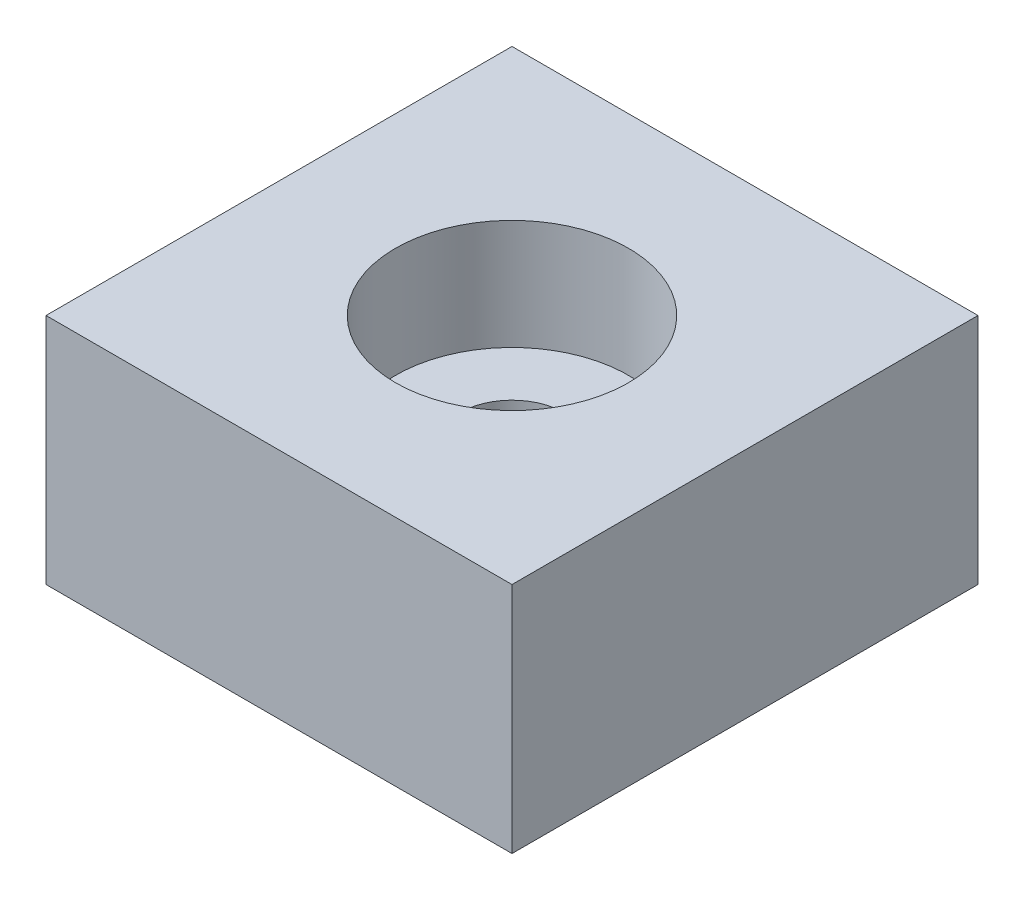
SolidWorks part; units mm, degrees
material "AISI 1020 Steel, Cold Rolled"
ref_plane "Front Plane" through (0, 0, 0) normal (0, 0, 1) x (1, 0, 0)
ref_plane "Top Plane" through (0, 0, 0) normal (0, 1, 0) x (1, 0, 0)
ref_plane "Right Plane" through (0, 0, 0) normal (1, 0, 0) x (0, 0, -1)
sketch "Sketch1" plane through (0, 0, 0) normal (0, 1, 0) x (1, 0, 0)
  line L1 (-19.05, -19.05) -> (19.05, -19.05)
  line L2 (-19.05, -19.05) -> (-19.05, 19.05)
  line L3 (-19.05, 19.05) -> (19.05, 19.05)
  line L4 (19.05, -19.05) -> (19.05, 19.05)
  line L5 (0, 19.05) -> (0, -19.05) construction
  line L6 (-19.05, 0) -> (19.05, 0) construction
  point P0 (0, 0)
  dimension "D1" = 38.1
extrude "Boss-Extrude1" add sketch "Sketch1" along normal blind 19.05
sketch "Sketch4" plane through (0, 19.05, 0) normal (0, 1, 0) x (1, 0, 0)
  point P0 (0, 0)
hole_wizard "M10x1.5 Tapped Hole1" positions "Sketch4" profile "Sketch3" tap size "M10x1.5" standard "ANSI Metric" end condition through all
sketch "Sketch3" plane through (0, 19.05, 0) normal (1, 0, 0) x (0, 0, 1)
  line L0 (0, 0) -> (0, 19.05)
  line L1 (0, 19.05) -> (4.25, 19.05)
  line L2 (4.25, 19.05) -> (4.25, 0)
  line L5 (4.25, 0) -> (0, 0)
  line L11 (0, -6.35) -> (0, 107.95) construction
  dimension "Thru Tap Drill Dia." = 8.5
  dimension "Thru Tap Drill Depth" = 19.05
cosmetic thread "Hole Thread1" parameters "D2"=10
sketch "Sketch5" plane through (0, 19.05, 0) normal (0, 1, 0) x (1, 0, 0)
  circle A0 centre (0, 0) radius 9.525
  dimension "D1" = 19.05
extrude "Cut-Extrude1" cut sketch "Sketch5" against normal blind 9
